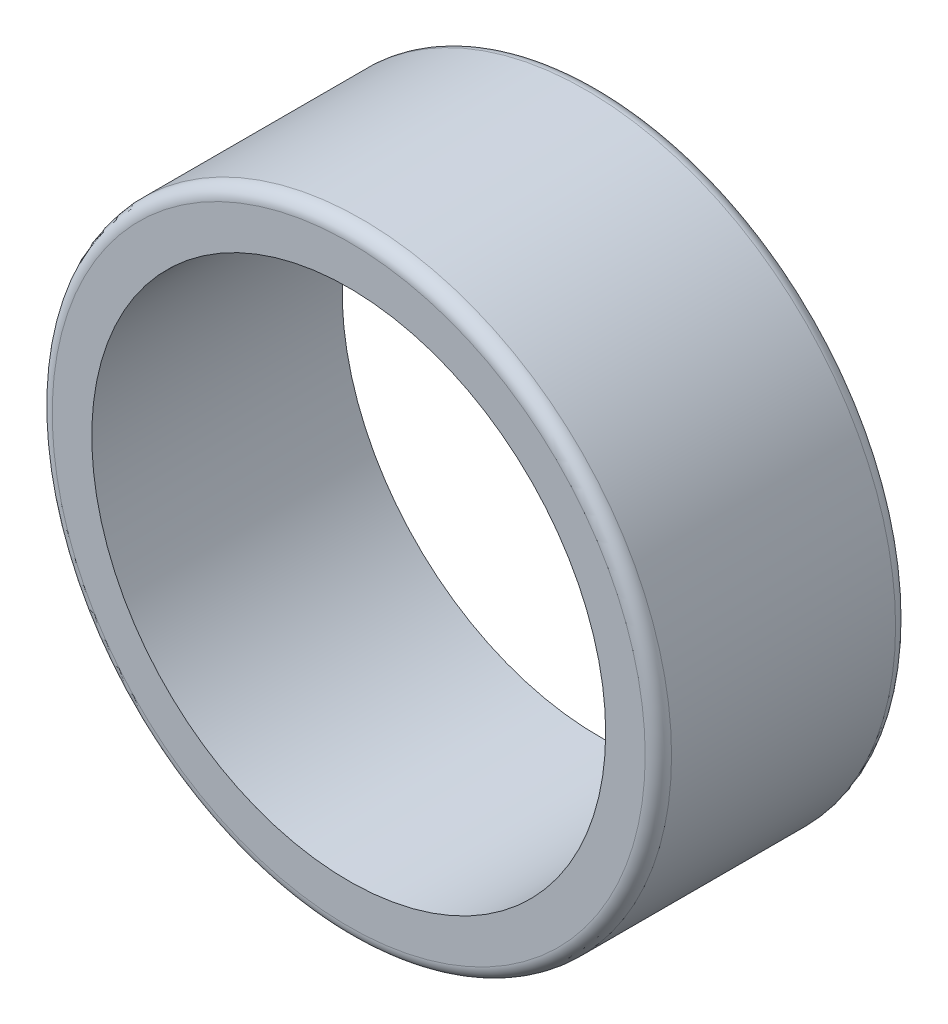
SolidWorks part; units mm, degrees
ref_plane "정면" through (0, 0, 0) normal (0, 0, 1) x (1, 0, 0)
ref_plane "윗면" through (0, 0, 0) normal (0, 1, 0) x (1, 0, 0)
ref_plane "우측면" through (0, 0, 0) normal (1, 0, 0) x (0, 0, -1)
sketch "스케치1" plane through (0, 0, 0) normal (0, 0, 1) x (1, 0, 0)
  circle A0 centre (0, 0) radius 9.75
  circle A1 centre (0, 0) radius 11.75
extrude "돌출1" add sketch "스케치1" along normal blind 9.5
fillet "필렛1" radius 0.5 1 edges at (11.75, 0, 9.5)
fillet "필렛2" radius 0.5 1 edges at (11.75, 0, 0)
